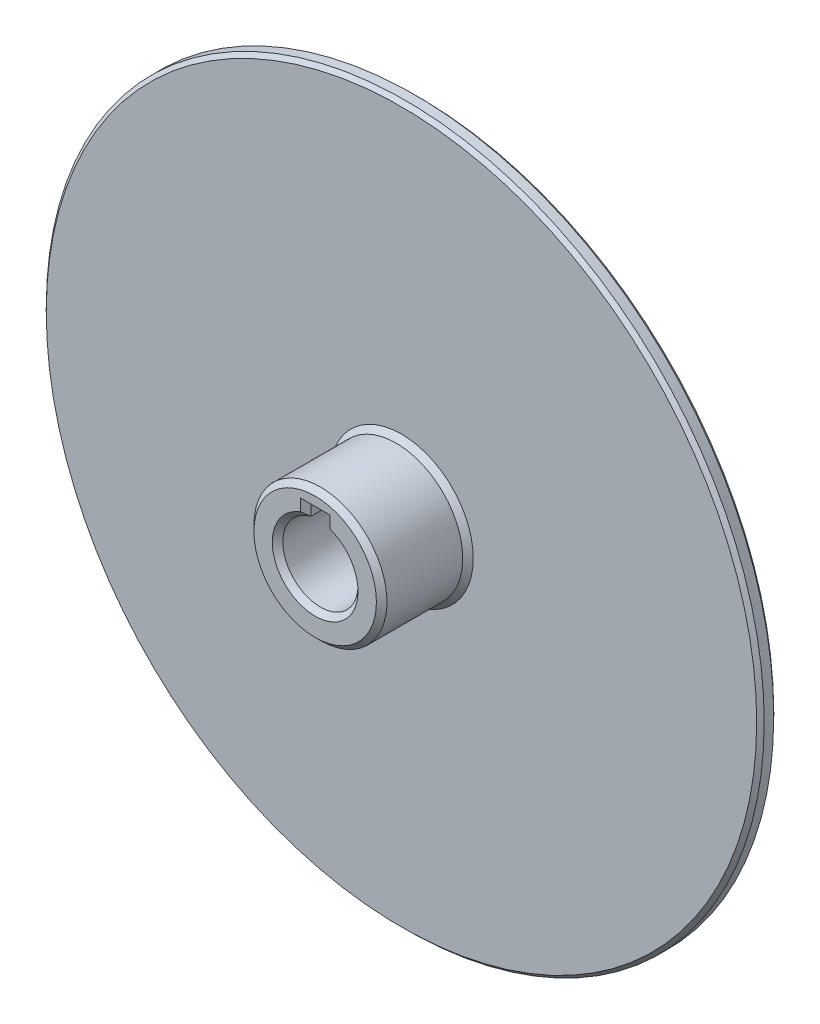
SolidWorks part; units mm, degrees
ref_plane "Front Plane" through (0, 0, 0) normal (0, 0, 1) x (1, 0, 0)
ref_plane "Top Plane" through (0, 0, 0) normal (0, 1, 0) x (1, 0, 0)
ref_plane "Right Plane" through (0, 0, 0) normal (1, 0, 0) x (0, 0, -1)
sketch "Sketch1" plane through (0, 0, 0) normal (0, 0, 1) x (1, 0, 0)
  circle A0 centre (0, 0) radius 121.3315
  dimension "D1" = 242.663
extrude "Boss-Extrude1" add sketch "Sketch1" along normal blind 5.7658
sketch "Sketch2" plane through (0, 0, 5.7658) normal (0, 0, 1) x (1, 0, 0)
  circle A0 centre (0, 0) radius 22.479
  dimension "D1" = 44.958
extrude "Boss-Extrude2" add sketch "Sketch2" along normal blind 29.1749
sketch "Sketch3" plane through (0, 0, 34.9407) normal (0, 0, 1) x (1, 0, 0)
  circle A0 centre (0, 0) radius 12.7
  dimension "D1" = 25.4
extrude "Cut-Extrude1" cut sketch "Sketch3" against normal through all both and the other way through all
sketch "Sketch4" plane through (0, 0, 34.9407) normal (0, 0, 1) x (1, 0, 0)
  line L1 (-3.175, 15.875) -> (3.175, 15.875)
  line L2 (-3.175, 15.875) -> (-3.175, 9.525)
  line L3 (-3.175, 9.525) -> (3.175, 9.525)
  line L4 (3.175, 15.875) -> (3.175, 9.525)
  line L5 (-3.175, 15.875) -> (3.175, 9.525) construction
  line L6 (-3.175, 9.525) -> (3.175, 15.875) construction
  circle A0 centre (0, 0) radius 12.7 construction
  point P0 (0, 12.7)
  point P7 (0, 0)
  dimension "D1" = 6.35
  dimension "D2" = 6.35
extrude "Cut-Extrude2" cut sketch "Sketch4" against normal through all both and the other way through all
chamfer "Chamfer1" distance 1.27 angle 45 2 edges at (121.3315, 0, 0) (121.3315, 0, 5.7658)
chamfer "Chamfer2" distance 1.778 angle 45 10 edges at (3.175, 14.0859, 0) (0, -12.7, 0) (-3.175, 14.0859, 0) (0, 15.875, 0) (3.175, 14.0859, 34.9407) (0, 15.875, 34.9407) (-3.175, 14.0859, 34.9407) (0, -12.7, 34.9407) (22.479, 0, 5.7658) (22.479, 0, 34.9407)
